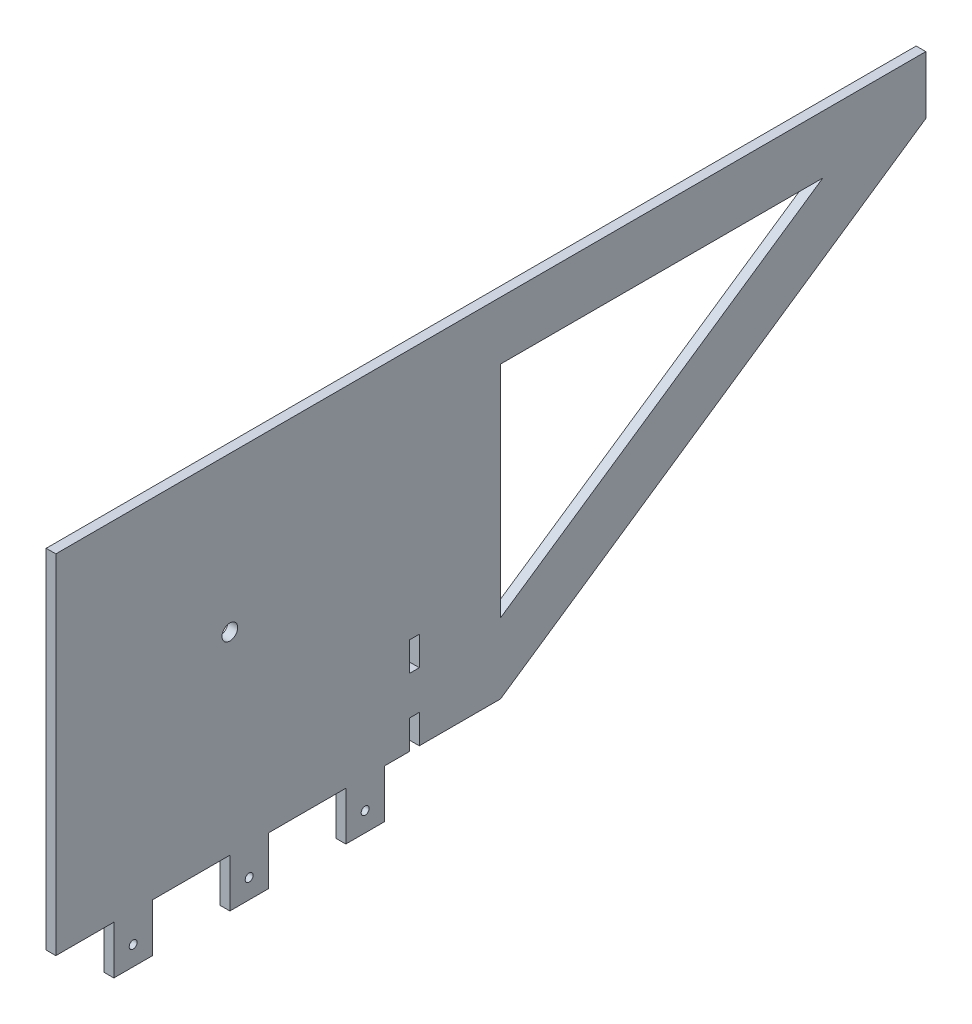
SolidWorks part; units mm, degrees
ref_plane "前基準面" through (0, 0, 0) normal (0, 0, 1) x (1, 0, 0)
ref_plane "上基準面" through (0, 0, 0) normal (0, 1, 0) x (1, 0, 0)
ref_plane "右基準面" through (0, 0, 0) normal (1, 0, 0) x (0, 0, -1)
sketch "草圖1" plane through (0, 0, 0) normal (1, 0, 0) x (0, 0, -1)
  line L0 (-70, -90) -> (-100, -90)
  line L1 (100, 90) -> (-100, 90)
  line L2 (100, 90) -> (100, -90)
  line L3 (100, -90) -> (70, -90)
  line L4 (-100, 90) -> (-100, -90)
  line L5 (0, -90) -> (0, 90) construction
  line L6 (100, 0) -> (-100, 0) construction
  line L8 (-70, -90) -> (-70, -115)
  line L9 (-70, -115) -> (-50, -115)
  line L10 (-50, -90) -> (-50, -115)
  line L12 (-10, -90) -> (-10, -115)
  line L13 (-10, -115) -> (10, -115)
  line L14 (10, -90) -> (10, -115)
  line L15 (70, -115) -> (50, -115)
  line L16 (70, -115) -> (70, -90)
  line L18 (50, -115) -> (50, -90)
  line L19 (-10, -90) -> (-50, -90)
  line L20 (50, -90) -> (10, -90)
  line L21 (-70, -95) -> (70, -95) construction
  circle A0 centre (-60, -105) radius 2.05
  circle A1 centre (0, -105) radius 2.05
  circle A2 centre (60, -105) radius 2.05
  point P0 (0, 0)
  point P28 (-60, -115)
  point P29 (0, -115)
  point P32 (60, -115)
  dimension "D9" = 4.1
  dimension "D1" = 200
  dimension "D2" = 180
  dimension "D3" = 20
  dimension "D4" = 25
  dimension "D5" = 40
  dimension "D6" = 40
  dimension "D7" = 30
  dimension "D8" = 20
  dimension "D10" = 10
extrude "填料-伸長1" add sketch "草圖1" along normal blind 5
sketch "草圖2" plane through (5, 0, 0) normal (1, 0, 0) x (0, 0, -1)
  line L0 (100, -90) -> (100, 90) construction
  line L1 (-50, -90) -> (-10, -90) construction
  circle A0 centre (-10, 10) radius 4.05
  dimension "D1" = 8.1
  dimension "D2" = 110
  dimension "D3" = 100
extrude "除料-伸長1" cut sketch "草圖2" against normal blind 10
sketch "草圖3" plane through (5, 0, 0) normal (1, 0, 0) x (0, 0, -1)
  line L0 (-100, -90) -> (-70, -90) construction
  line L1 (83, -40) -> (88, -40)
  line L2 (83, -40) -> (83, -55)
  line L3 (83, -55) -> (88, -55)
  line L4 (88, -40) -> (88, -55)
  line L5 (83, -75) -> (88, -75)
  line L6 (83, -75) -> (83, -90)
  line L7 (83, -90) -> (88, -90)
  line L8 (88, -75) -> (88, -90)
  line L10 (100, -90) -> (100, 90) construction
  point P8 (-72.6204, -54.4446)
  point P9 (0, 0)
  point P10 (-80.1329, -90)
  dimension "D1" = 15
  dimension "D2" = 5
  dimension "D3" = 50
  dimension "D4" = 12
extrude "除料-伸長2" cut sketch "草圖3" against normal through all
sketch "草圖4" plane through (0, 0, 0) normal (-1, 0, 0) x (0, 0, 1)
  line L0 (-100, 90) -> (-350, 90)
  line L1 (-350, 90) -> (-350, 60)
  line L2 (-350, 60) -> (-130, -90)
  line L3 (-130, -90) -> (-100, -90)
  line L4 (-88, -90) -> (-100, -90) construction
  line L5 (-100, 90) -> (-100, -90)
  line L6 (-130, 60) -> (-130, -53.6904)
  line L7 (-130, -53.6904) -> (-130, -53.6904)
  line L8 (-296.7459, 60) -> (-130, -53.6904)
  line L9 (-296.7459, 60) -> (-296.7459, 60)
  line L10 (-130, 60) -> (-296.7459, 60)
  point P8 (-142.542, -90)
  dimension "D1" = 30
  dimension "D2" = 250
  dimension "D3" = 30
  dimension "D4" = 30
extrude "填料-伸長2" add sketch "草圖4" against normal blind 5
